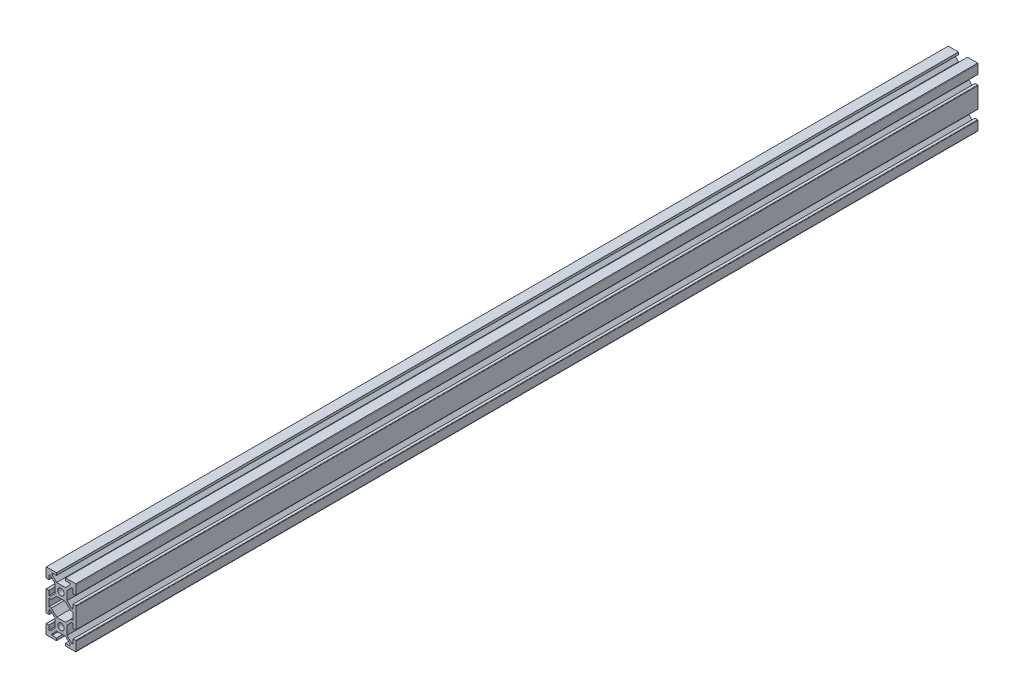
SolidWorks part; units mm, degrees
ref_plane "Front Plane" through (0, 0, 0) normal (0, 0, 1) x (1, 0, 0)
ref_plane "Top Plane" through (0, 0, 0) normal (0, 1, 0) x (1, 0, 0)
ref_plane "Right Plane" through (0, 0, 0) normal (1, 0, 0) x (0, 0, -1)
sketch "草图1" plane through (0, 0, 0) normal (0, 0, 1) x (1, 0, 0)
  line L0 (-10, 19) -> (-10, 13.3)
  line L1 (-9.7, 13) -> (-8, 13)
  line L2 (-8, 13) -> (-8, 16)
  line L3 (-8, 16) -> (-7.0607, 16)
  line L4 (-7.0607, 16) -> (-4, 12.9393)
  line L5 (-4, 12.9393) -> (-4, 7.0607)
  line L6 (-4, 7.0607) -> (-7.0607, 4)
  line L7 (-7.0607, 4) -> (-8, 4)
  line L8 (-8, 4) -> (-8, 7)
  line L9 (-8, 7) -> (-9.7, 7)
  line L10 (-10, 6.7) -> (-10, -6.7)
  line L11 (-9.7, -7) -> (-8, -7)
  line L12 (-8, -7) -> (-8, -4)
  line L13 (-8, -4) -> (-7.0607, -4)
  line L14 (-7.0607, -4) -> (-4, -7.0607)
  line L15 (-4, -7.0607) -> (-4, -12.9393)
  line L16 (-4, -12.9393) -> (-7.0607, -16)
  line L17 (-7.0607, -16) -> (-8, -16)
  line L18 (-8, -16) -> (-8, -13)
  line L19 (-8, -13) -> (-9.7, -13)
  line L20 (-10, -13.3) -> (-10, -19)
  line L21 (-9.8, -19.6) -> (-3, -19.6)
  line L22 (-3, -19.6) -> (-3, -18)
  line L23 (-3, -18) -> (-6, -18)
  line L24 (-6, -18) -> (-6, -17.0607)
  line L25 (-6, -17.0607) -> (-2.9393, -14)
  line L26 (-2.9393, -14) -> (2.9393, -14)
  line L27 (2.9393, -14) -> (6, -17.0607)
  line L28 (6, -17.0607) -> (6, -18)
  line L29 (6, -18) -> (3, -18)
  line L30 (3, -18) -> (3, -19.6)
  line L31 (3, -19.6) -> (9.8, -19.6)
  line L32 (10, -19) -> (10, -13.3)
  line L33 (9.7, -13) -> (8, -13)
  line L34 (8, -13) -> (8, -16)
  line L35 (8, -16) -> (7.0607, -16)
  line L36 (7.0607, -16) -> (4, -12.9393)
  line L37 (4, -12.9393) -> (4, -7.0607)
  line L38 (4, -7.0607) -> (7.0607, -4)
  line L39 (7.0607, -4) -> (8, -4)
  line L40 (8, -4) -> (8, -7)
  line L41 (8, -7) -> (9.7, -7)
  line L42 (10, -6.7) -> (10, 6.7)
  line L43 (9.7, 7) -> (8, 7)
  line L44 (8, 7) -> (8, 4)
  line L45 (8, 4) -> (7.0607, 4)
  line L46 (7.0607, 4) -> (4, 7.0607)
  line L47 (4, 7.0607) -> (4, 12.9393)
  line L48 (4, 12.9393) -> (7.0607, 16)
  line L49 (7.0607, 16) -> (8, 16)
  line L50 (8, 16) -> (8, 13)
  line L51 (8, 13) -> (9.7, 13)
  line L52 (10, 13.3) -> (10, 19)
  line L53 (9.8, 19.6) -> (3, 19.6)
  line L54 (3, 19.6) -> (3, 18)
  line L55 (3, 18) -> (6, 18)
  line L56 (6, 18) -> (6, 17.0607)
  line L57 (6, 17.0607) -> (2.9393, 14)
  line L58 (2.9393, 14) -> (-2.9393, 14)
  line L59 (-2.9393, 14) -> (-6, 17.0607)
  line L60 (-6, 17.0607) -> (-6, 18)
  line L61 (-6, 18) -> (-3, 18)
  line L62 (-3, 18) -> (-3, 19.6)
  line L63 (-3, 19.6) -> (-9.8, 19.6)
  line L64 (-8, -2.5) -> (-6.4393, -2.5)
  line L65 (-6.4393, -2.5) -> (-2.9393, -6)
  line L66 (-2.9393, -6) -> (2.9393, -6)
  line L67 (2.9393, -6) -> (6.4393, -2.5)
  line L68 (6.4393, -2.5) -> (8, -2.5)
  line L69 (8, -2.5) -> (8, 2.5)
  line L70 (8, 2.5) -> (6.4393, 2.5)
  line L71 (6.4393, 2.5) -> (2.9393, 6)
  line L72 (2.9393, 6) -> (-2.9393, 6)
  line L73 (-2.9393, 6) -> (-6.4393, 2.5)
  line L74 (-6.4393, 2.5) -> (-8, 2.5)
  line L75 (-8, 2.5) -> (-8, -2.5)
  arc A0 (-10, 13.3) -> (-9.7, 13) centre (-9.7, 13.3) ccw
  arc A1 (-9.7, 7) -> (-10, 6.7) centre (-9.7, 6.7) ccw
  arc A2 (-10, -6.7) -> (-9.7, -7) centre (-9.7, -6.7) ccw
  arc A3 (-9.7, -13) -> (-10, -13.3) centre (-9.7, -13.3) ccw
  arc A4 (-10, -19) -> (-9.8, -19.6) centre (-9, -19) ccw
  arc A5 (9.8, -19.6) -> (10, -19) centre (9, -19) ccw
  arc A6 (10, -13.3) -> (9.7, -13) centre (9.7, -13.3) ccw
  arc A7 (9.7, -7) -> (10, -6.7) centre (9.7, -6.7) ccw
  arc A8 (10, 6.7) -> (9.7, 7) centre (9.7, 6.7) ccw
  arc A9 (9.7, 13) -> (10, 13.3) centre (9.7, 13.3) ccw
  arc A10 (10, 19) -> (9.8, 19.6) centre (9, 19) ccw
  arc A11 (-9.8, 19.6) -> (-10, 19) centre (-9, 19) ccw
  circle A12 centre (0, -10) radius 2.1
  circle A13 centre (0, 10) radius 2.1
extrude "凸台-拉伸1" add sketch "草图1" against normal blind 600
ref_plane "基准面1" through (0, 0, -100) normal (0, 0, 1) x (1, 0, 0)
ref_plane "基准面2" through (0, 10, 0) normal (0, 1, 0) x (1, 0, 0)
ref_plane "基准面3" through (0, 0, 0) normal (0, 0, 1) x (1, 0, 0)
ref_plane "基准面4" through (0, 0, 0) normal (1, 0, 0) x (0, 0, -1)
ref_plane "基准面5" through (0, 19.6, 0) normal (0, 1, 0) x (1, 0, 0)
ref_plane "基准面6" through (0, 0, 0) normal (1, 0, 0) x (0, 0, -1)
ref_plane "基准面7" through (0, 0, 0) normal (1, 0, 0) x (0, 0, -1)
ref_plane "基准面8" through (0, 0, 0) normal (1, 0, 0) x (0, 0, -1)
